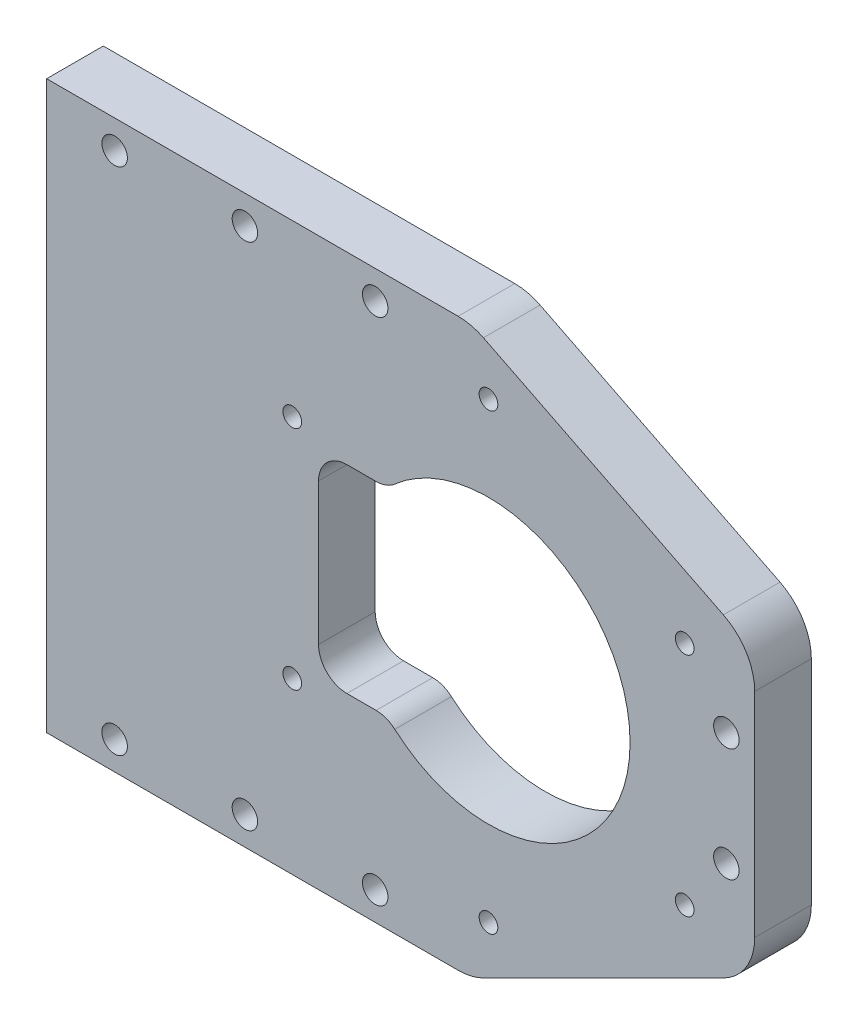
SolidWorks part; units mm, degrees
material "7079 Alloy"
ref_plane "Front Plane" through (0, 0, 0) normal (0, 0, 1) x (1, 0, 0)
ref_plane "Top Plane" through (0, 0, 0) normal (0, 1, 0) x (1, 0, 0)
ref_plane "Right Plane" through (0, 0, 0) normal (1, 0, 0) x (0, 0, -1)
sketch "Sketch1" plane through (0, 0, 0) normal (0, 0, 1) x (1, 0, 0)
  line L0 (0, 0) -> (75, 0) construction
  line L1 (0, -50) -> (75, -50)
  line L2 (75, 50) -> (125, 25)
  line L3 (0, -50) -> (0, 50)
  line L4 (0, 50) -> (75, 50)
  line L5 (125, -25) -> (125, 25)
  line L6 (75, -50) -> (125, -25)
  line L7 (75, 0) -> (75, -50) construction
  point P3 (125, 50)
  point P5 (125, -50)
  dimension "D1" = 125
  dimension "D2" = 100
  dimension "D4" = 25
  dimension "D3" = 25
extrude "Extrude1" add sketch "Sketch1" along normal blind 10
sketch "Sketch2" plane through (0, 0, 10) normal (0, 0, 1) x (1, 0, 0)
  line L0 (125, 0) -> (78, 0) construction
  line L1 (125, -25) -> (125, 25) construction
  line L2 (78, 0) -> (48, 0) construction
  line L4 (60.1464, -17.5) -> (48, -17.5)
  line L6 (60.1464, 17.5) -> (48, 17.5)
  line L7 (48, -17.5) -> (48, 17.5)
  arc A0 (60.1464, -17.5) -> (60.1464, 17.5) centre (78, 0) ccw
  point P11 (48, 0)
  dimension "D2" = 50
  dimension "D1" = 47
  dimension "D3" = 30
  dimension "D4" = 35
extrude "Cut-Extrude1" cut sketch "Sketch2" against normal blind 20
sketch "Sketch3" plane through (0, 0, 0) normal (0, 0, -1) x (-1, 0, 0)
  line L0 (-78, 0) -> (-118, 0) construction
  line L1 (-118, 0) -> (-78, 0) construction
  line L2 (-78, 0) -> (-112.641, 20) construction
  circle A0 centre (-78, 0) radius 40 construction
  circle A1 centre (-112.641, 20) radius 1.65
  circle A2 centre (-78, 40) radius 1.65
  circle A3 centre (-43.359, 20) radius 1.65
  circle A4 centre (-43.359, -20) radius 1.65
  circle A5 centre (-78, -40) radius 1.65
  circle A6 centre (-112.641, -20) radius 1.65
  dimension "D2" = 80
  dimension "D3" = 3.3
  dimension "D1" = 30
  dimension "D4" = 6
extrude "Cut-Extrude2" cut sketch "Sketch3" against normal blind 10
sketch "Sketch4" plane through (0, 0, 0) normal (-1, 0, 0) x (0, 0, 1)
  line L0 (5, -50) -> (5, 50) construction
  line L1 (10, -50) -> (0, -50) construction
  line L2 (10, 50) -> (0, 50) construction
  line L3 (0, 0) -> (10, 0) construction
  line L4 (10, 50) -> (10, -50) construction
  circle A0 centre (5, -37.5) radius 1.65
  circle A1 centre (5, -12.5) radius 1.65
  circle A2 centre (5, 12.5) radius 1.65
  circle A3 centre (5, 37.5) radius 1.65
  dimension "D1" = 3.3
  dimension "D3" = 25
  dimension "D2" = 12.5
extrude "Cut-Extrude3" cut sketch "Sketch4" against normal blind 15
fillet "Fillet1" radius 10 4 edges at (75, 50, 5) (125, 25, 5) (125, -25, 5) (75, -50, 5)
fillet "Fillet3" radius 5 4 edges at (60.1464, 17.5, 5) (60.1464, -17.5, 5) (48, -17.5, 5) (48, 17.5, 5)
sketch "Sketch7" plane through (0, 0, 0) normal (0, 0, -1) x (-1, 0, 0)
  line L0 (0, -45) -> (-70, -45) construction
  line L1 (0, 50) -> (0, -50) construction
  line L2 (-35, -45) -> (-35, -50) construction
  line L3 (0, -50) -> (-72.6393, -50) construction
  line L4 (0, 0) -> (-48, 0) construction
  line L5 (-48, 12.5) -> (-48, -12.5) construction
  circle A0 centre (-35, -45) radius 1.5
  circle A1 centre (-12, -45) radius 1.5
  circle A2 centre (-58, -45) radius 1.5
  circle A3 centre (-35, 45) radius 1.5
  circle A4 centre (-58, 45) radius 1.5
  circle A5 centre (-12, 45) radius 1.5
  dimension "D2" = 3
  dimension "D3" = 23
  dimension "D1" = 70
  dimension "D4" = 5
extrude "Cut-Extrude4" cut sketch "Sketch7" against normal blind 10
hole_wizard "CSK for M4 Flat Head Machine Screw2" positions "Sketch9" profile "Sketch8" countersink size "M4" standard "Ansi Metric" end condition through all
sketch "Sketch9" plane through (0, 0, 0) normal (0, 0, -1) x (-1, 0, 0)
  point P1 (-58, -45)
  point P4 (-35, -45)
  point P7 (-12, -45)
  point P10 (-58, 45)
  point P13 (-35, 45)
  point P16 (-12, 45)
sketch "Sketch8" plane through (58, -45, 0) normal (1, 0, 0) x (0, 1, 0)
  line L0 (0, 0) -> (0, 10)
  line L1 (0, 10) -> (2.25, 10)
  line L2 (2.25, 10) -> (2.25, 2.45)
  line L3 (2.25, 2.45) -> (4.7, 0)
  line L5 (4.7, 0) -> (0, 0)
  line L6 (-2.25, 2.45) -> (-4.7, 0) construction
  line L11 (0, -6.35) -> (0, 107.95) construction
  dimension "Thru Hole Dia." = 4.5
  dimension "Thru Hole Depth" = 10
  dimension "Near C'Sink Dia." = 9.4
  dimension "Near C'Sink Angle" = 90
sketch "Sketch10" plane through (0, 0, 0) normal (0, 0, -1) x (-1, 0, 0)
  line L0 (-125, 0) -> (-118.8358, 0) construction
  line L1 (-125, -18.8197) -> (-125, 18.8197) construction
  circle A0 centre (-120, -10) radius 2.25
  circle A1 centre (-120, 10) radius 2.25
  dimension "D1" = 4.5
  dimension "D2" = 5
  dimension "D3" = 10
extrude "Cut-Extrude5" cut sketch "Sketch10" against normal blind 10
hole_wizard "CSK for M4 Flat Head Machine Screw3" positions "Sketch12" profile "Sketch11" countersink size "M4" standard "Ansi Metric" end condition through all
sketch "Sketch12" plane through (0, 0, 0) normal (0, 0, -1) x (-1, 0, 0)
  point P1 (-120, -10)
  point P4 (-120, 10)
sketch "Sketch11" plane through (120, -10, 0) normal (1, 0, 0) x (0, 1, 0)
  line L0 (0, 0) -> (0, 10)
  line L1 (0, 10) -> (2.25, 10)
  line L2 (2.25, 10) -> (2.25, 2.45)
  line L3 (2.25, 2.45) -> (4.7, 0)
  line L5 (4.7, 0) -> (0, 0)
  line L6 (-2.25, 2.45) -> (-4.7, 0) construction
  line L11 (0, -6.35) -> (0, 107.95) construction
  dimension "Thru Hole Dia." = 4.5
  dimension "Thru Hole Depth" = 10
  dimension "Near C'Sink Dia." = 9.4
  dimension "Near C'Sink Angle" = 90
